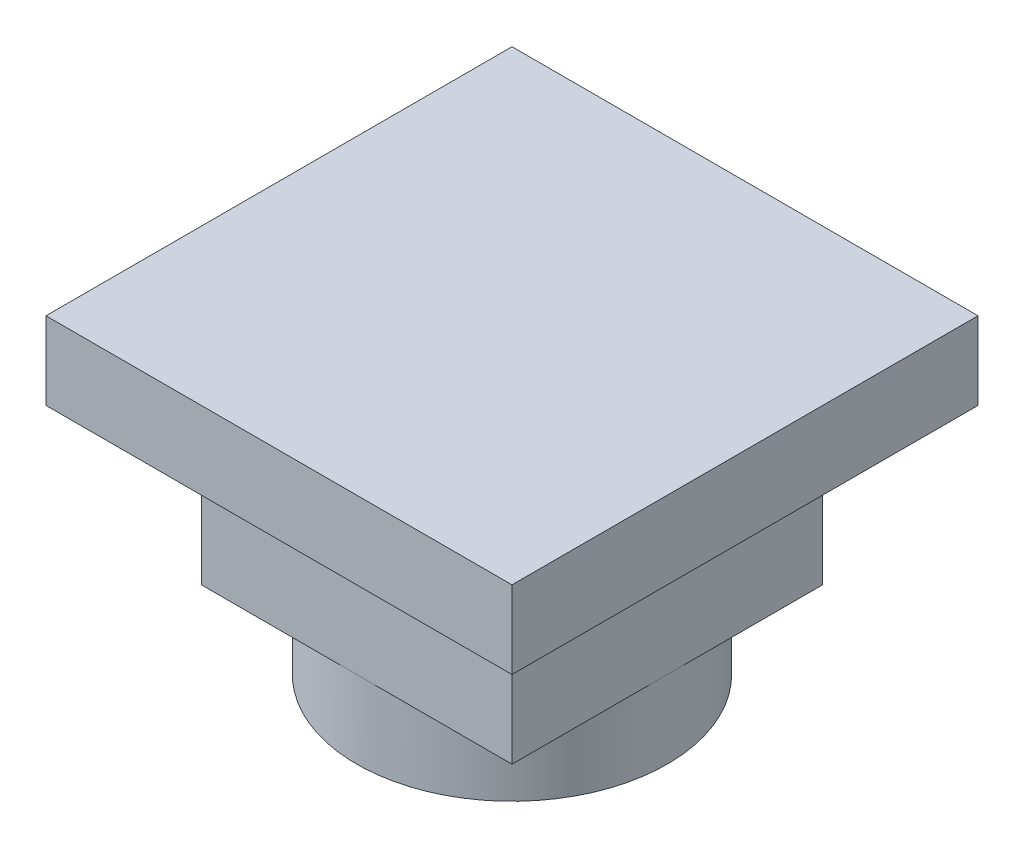
SolidWorks part; units mm, degrees
ref_plane "Front Plane" through (0, 0, 0) normal (0, 0, 1) x (1, 0, 0)
ref_plane "Top Plane" through (0, 0, 0) normal (0, 1, 0) x (1, 0, 0)
ref_plane "Right Plane" through (0, 0, 0) normal (1, 0, 0) x (0, 0, -1)
sketch "Sketch1" plane through (0, 0, 0) normal (0, 1, 0) x (1, 0, 0)
  line L1 (-0.5, -0.5) -> (0.5, -0.5)
  line L2 (-0.5, -0.5) -> (-0.5, 0.5)
  line L3 (-0.5, 0.5) -> (0.5, 0.5)
  line L4 (0.5, -0.5) -> (0.5, 0.5)
  line L5 (-0.5, -0.5) -> (0.5, 0.5) construction
  line L6 (-0.5, 0.5) -> (0.5, -0.5) construction
  point P0 (0, 0)
  dimension "D1" = 1
  dimension "D2" = 1
extrude "Boss-Extrude1" add sketch "Sketch1" along normal blind 0.5
sketch "Sketch2" plane through (0, 0.5, 0) normal (0, 1, 0) x (1, 0, 0)
  line L1 (-0.75, -0.75) -> (0.75, -0.75)
  line L2 (-0.75, -0.75) -> (-0.75, 0.75)
  line L3 (-0.75, 0.75) -> (0.75, 0.75)
  line L4 (0.75, -0.75) -> (0.75, 0.75)
  line L5 (-0.75, -0.75) -> (0.75, 0.75) construction
  line L6 (-0.75, 0.75) -> (0.75, -0.75) construction
  point P0 (0, 0)
  dimension "D1" = 1.5
  dimension "D2" = 1.5
extrude "Boss-Extrude2" add sketch "Sketch2" along normal blind 0.25
sketch "Sketch3" plane through (0, 0, 0) normal (0, -1, 0) x (1, 0, 0)
  circle A0 centre (0, 0) radius 0.5
  dimension "D1" = 1
extrude "Boss-Extrude3" add sketch "Sketch3" along normal blind 0.25
scale "Scale1" scale about centroid uniform scaling yes scale factor 6
